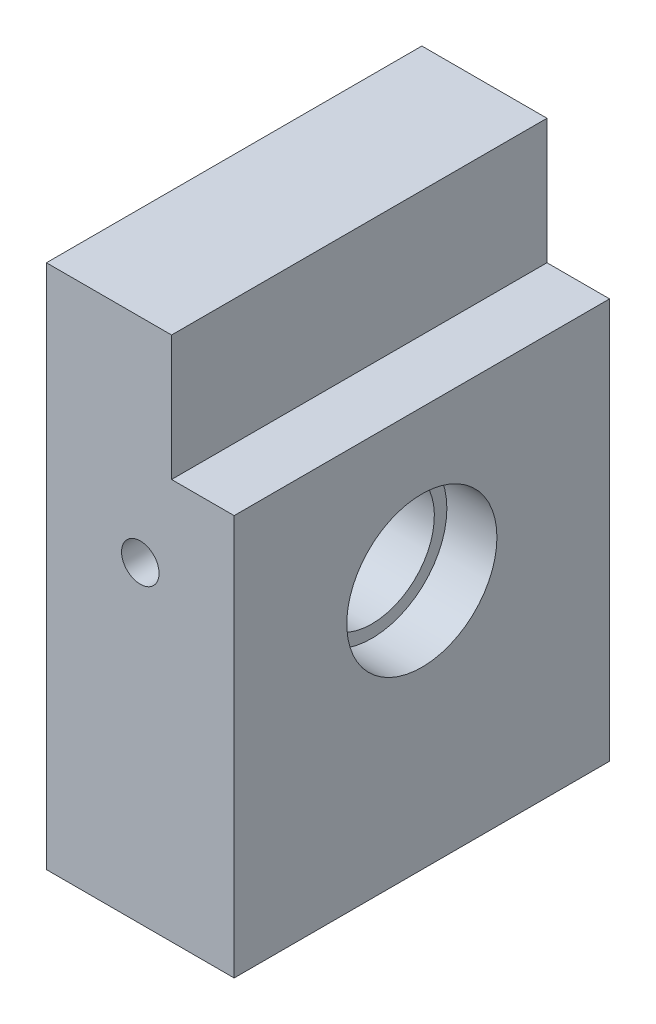
SolidWorks part; units mm, degrees
material "AISI 1045 Aço, trefilado"
ref_plane "Plano frontal" through (0, 0, 0) normal (0, 0, 1) x (1, 0, 0)
ref_plane "Plano superior" through (0, 0, 0) normal (0, 1, 0) x (1, 0, 0)
ref_plane "Plano direito" through (0, 0, 0) normal (1, 0, 0) x (0, 0, -1)
sketch "Esboço2" plane through (0, 0, 0) normal (0, 0, 1) x (1, 0, 0)
  line L0 (0, 0) -> (0, -42)
  line L1 (0, -42) -> (15, -42)
  line L2 (15, -42) -> (15, -10)
  line L3 (15, -10) -> (10, -10)
  line L4 (10, -10) -> (10, 0)
  line L5 (10, 0) -> (0, 0)
  dimension "D1" = 15
  dimension "D2" = 42
  dimension "D3" = 5
  dimension "D4" = 10
extrude "Ressalto-extrusão1" add sketch "Esboço2" along normal blind 30
sketch "Esboço4" plane through (15, 0, 0) normal (1, 0, 0) x (0, 0, -1)
  line L0 (-30, -42) -> (0, -42) construction
  line L1 (0, -42) -> (0, -10) construction
  circle A0 centre (-15, -22) radius 6
  dimension "D1" = 12
  dimension "D2" = 20
  dimension "D3" = 15
extrude "Corte-extrusão1" cut sketch "Esboço4" against normal blind 4
sketch "Esboço5" plane through (0, 0, 0) normal (-1, 0, 0) x (0, 0, 1)
  line L0 (30, -42) -> (0, -42) construction
  line L1 (30, 0) -> (30, -42) construction
  circle A0 centre (15, -22) radius 5
  dimension "D1" = 10
  dimension "D2" = 20
  dimension "D3" = 15
extrude "Corte-extrusão2" cut sketch "Esboço5" against normal blind 11
sketch "Esboço6" plane through (0, 0, 30) normal (0, 0, 1) x (1, 0, 0)
  line L0 (15, -42) -> (15, -10) construction
  line L1 (10, 0) -> (0, 0) construction
  circle A0 centre (7.5, -17) radius 1.5
  dimension "D1" = 3
  dimension "D2" = 7.5
  dimension "D3" = 17
extrude "Corte-extrusão3" cut sketch "Esboço6" against normal through all
sketch "Esboço7" plane through (0, -42, 0) normal (0, -1, 0) x (1, 0, 0)
  line L0 (0, 30) -> (15, 30) construction
  line L1 (0, 0) -> (15, 0) construction
  circle A0 centre (7.0977, 24) radius 2.5
  circle A1 centre (7.0977, 6) radius 2.5
  dimension "D1" = 5
  dimension "D2" = 5
  dimension "D3" = 18
  dimension "D4" = 6
  dimension "D5" = 6
extrude "Corte-extrusão4" cut sketch "Esboço7" against normal blind 9
sketch "Esboço8" plane through (0, -42, 0) normal (0, -1, 0) x (1, 0, 0)
  circle A0 centre (7.0977, 24) radius 2
  circle A1 centre (7.0977, 6) radius 2
  dimension "D1" = 4
  dimension "D2" = 4
extrude "Corte-extrusão5" cut sketch "Esboço8" against normal blind 11
